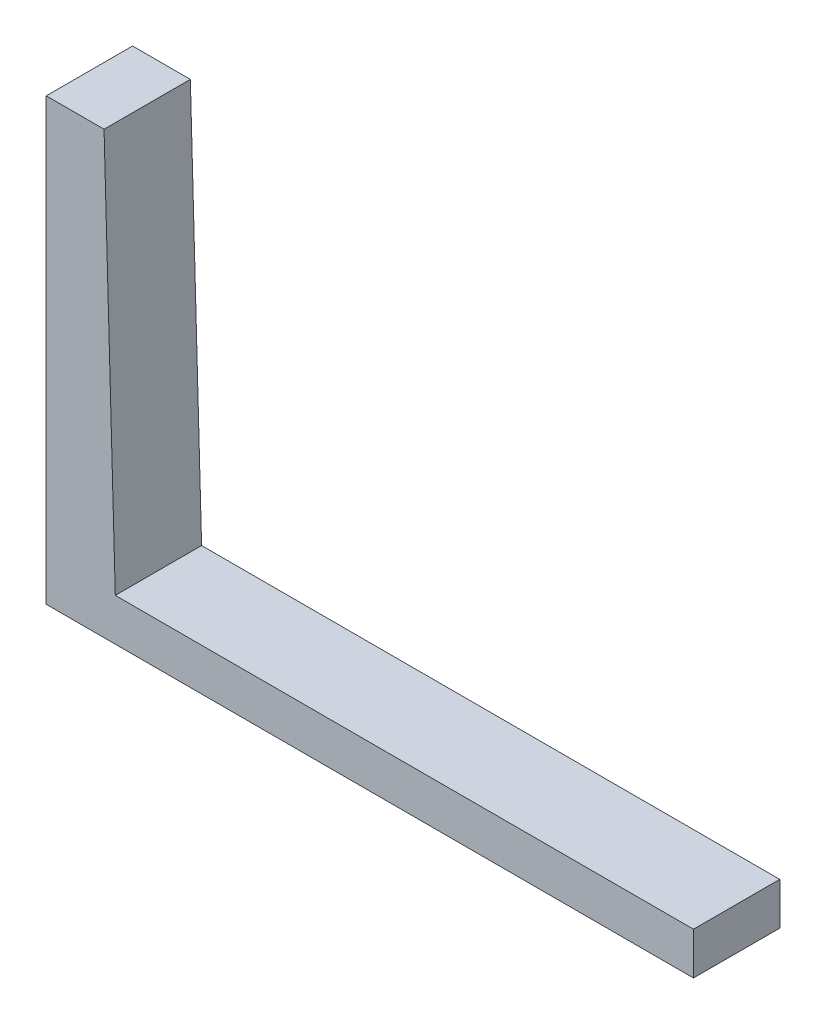
SolidWorks part; units mm, degrees
ref_plane "前视基准面" through (0, 0, 0) normal (0, 0, 1) x (1, 0, 0)
ref_plane "上视基准面" through (0, 0, 0) normal (0, 1, 0) x (1, 0, 0)
ref_plane "右视基准面" through (0, 0, 0) normal (1, 0, 0) x (0, 0, -1)
other "Configuration Table"
sketch "草图1" plane through (0, 0, 0) normal (0, 0, 1) x (1, 0, 0)
  line L0 (0, 0) -> (4315.6784, 0) construction
  line L1 (0, 0) -> (0, -4315.6784) construction
  line L2 (-37.5, 0) -> (37.5, 0)
  line L3 (-37.5, 0) -> (-37.5, 51.031)
  line L7 (-37.5, 51.031) -> (-30.8014, 51.031)
  line L8 (-30.8014, 51.031) -> (-29.4982, 4.8988)
  line L9 (-29.4982, 4.8988) -> (37.5, 4.8988)
  line L10 (37.5, 4.8988) -> (37.5, 0)
  point P8 (0, 0)
  dimension "D1" = 75
extrude "凸台-拉伸1" add sketch "草图1" along normal mid plane 10
